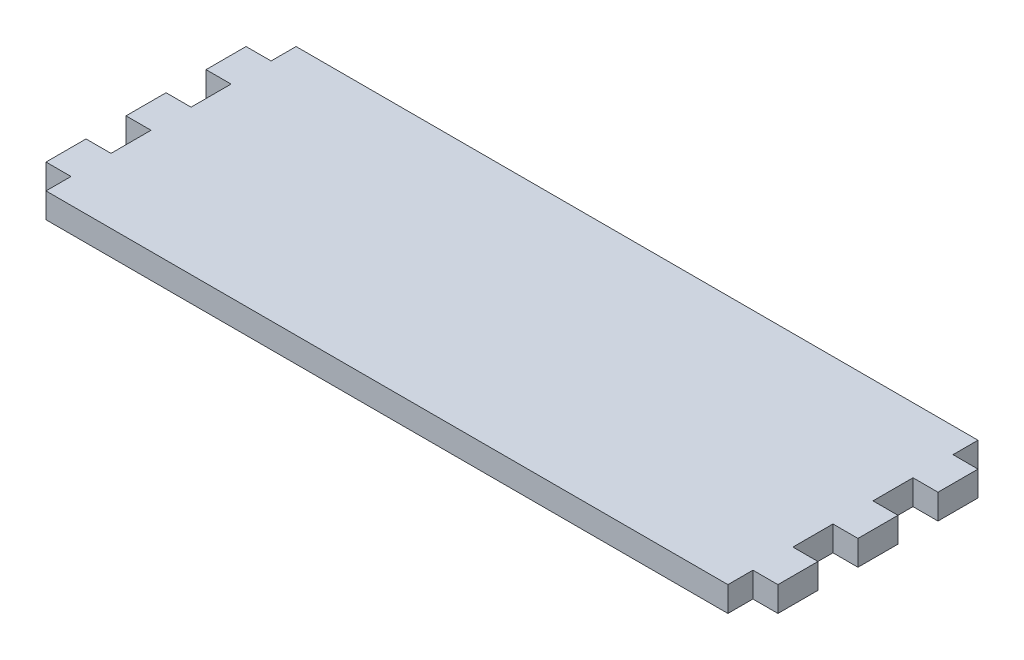
SolidWorks part; units mm, degrees
ref_plane "Front" through (0, 0, 0) normal (0, 0, 1) x (1, 0, 0)
ref_plane "Top" through (0, 0, 0) normal (0, 1, 0) x (1, 0, 0)
ref_plane "Right" through (0, 0, 0) normal (1, 0, 0) x (0, 0, -1)
sketch "Esboço1" plane through (0, 0, 0) normal (0, 1, 0) x (1, 0, 0)
  line L0 (-65.5193, 7.7418) -> (-62.5193, 7.7418)
  line L1 (-62.5193, 7.7418) -> (-62.5193, 10.7418)
  line L2 (-62.5193, 10.7418) -> (19.2807, 10.7418)
  line L3 (19.2807, 10.7418) -> (19.2807, 7.7418)
  line L4 (19.2807, 7.7418) -> (22.2807, 7.7418)
  line L6 (22.2807, -16.2582) -> (19.2807, -16.2582)
  line L7 (19.2807, -16.2582) -> (19.2807, -19.2582)
  line L8 (19.2807, -19.2582) -> (-62.5193, -19.2582)
  line L9 (-62.5193, -19.2582) -> (-62.5193, -16.2582)
  line L10 (-62.5193, -16.2582) -> (-65.5193, -16.2582)
  line L16 (-65.5193, -1.8582) -> (-65.5193, -6.6582)
  line L17 (-65.5193, -6.6582) -> (-62.5193, -6.6582)
  line L18 (-62.5193, -6.6582) -> (-62.5193, -11.4582)
  line L19 (-62.5193, -11.4582) -> (-65.5193, -11.4582)
  line L24 (-65.5193, -11.4582) -> (-65.5193, -16.2582)
  line L31 (-65.5193, -1.8582) -> (-62.5193, -1.8582)
  line L32 (-62.5193, -1.8582) -> (-62.5193, 2.9418)
  line L33 (-62.5193, 2.9418) -> (-65.5193, 2.9418)
  line L34 (-65.5193, 2.9418) -> (-65.5193, 7.7418)
  line L40 (22.2807, 7.7418) -> (22.2807, 2.9418)
  line L41 (22.2807, 2.9418) -> (19.2807, 2.9418)
  line L42 (19.2807, 2.9418) -> (19.2807, -1.8582)
  line L43 (19.2807, -1.8582) -> (22.2807, -1.8582)
  line L48 (22.2807, -1.8582) -> (22.2807, -6.6582)
  line L49 (22.2807, -6.6582) -> (19.2807, -6.6582)
  line L50 (19.2807, -6.6582) -> (19.2807, -11.4582)
  line L51 (19.2807, -11.4582) -> (22.2807, -11.4582)
  line L56 (22.2807, -11.4582) -> (22.2807, -16.2582)
  point P2 (-65.3117, 7.7418)
  point P13 (22.2807, -22.2582)
  point P14 (-65.7438, -16.2582)
  point P15 (-65.5214, -4.4551)
  point P16 (22.2807, -22.2582)
  point P17 (22.2807, -22.2582)
  point P18 (22.2807, -16.6144)
  point P19 (22.2807, -4.5759)
  point P20 (22.613, 7.7418)
  dimension "D12" = 10.7418
  dimension "D13" = 4.8
  dimension "D14" = 4.8
  dimension "D15" = 4.8
  dimension "D16" = 3
  dimension "D17" = 3
  dimension "D20" = 3
  dimension "D21" = 3
  dimension "D22" = 4.8
  dimension "D2" = 81.8
  dimension "D3" = 24
  dimension "D4" = 3
  dimension "D5" = 3
  dimension "D6" = 3
  dimension "D7" = 3
  dimension "D8" = 3
  dimension "D9" = 3
  dimension "D10" = 3
  dimension "D11" = 3
  dimension "D23" = 4.8
  dimension "D24" = 4.8
  dimension "D28" = 4.8
  dimension "D33" = 4.8
  dimension "D41" = 3
  dimension "D42" = 3
  dimension "D45" = 3
  dimension "D46" = 3
extrude "Ressalto-extrusão1" add sketch "Esboço1" along normal blind 3
